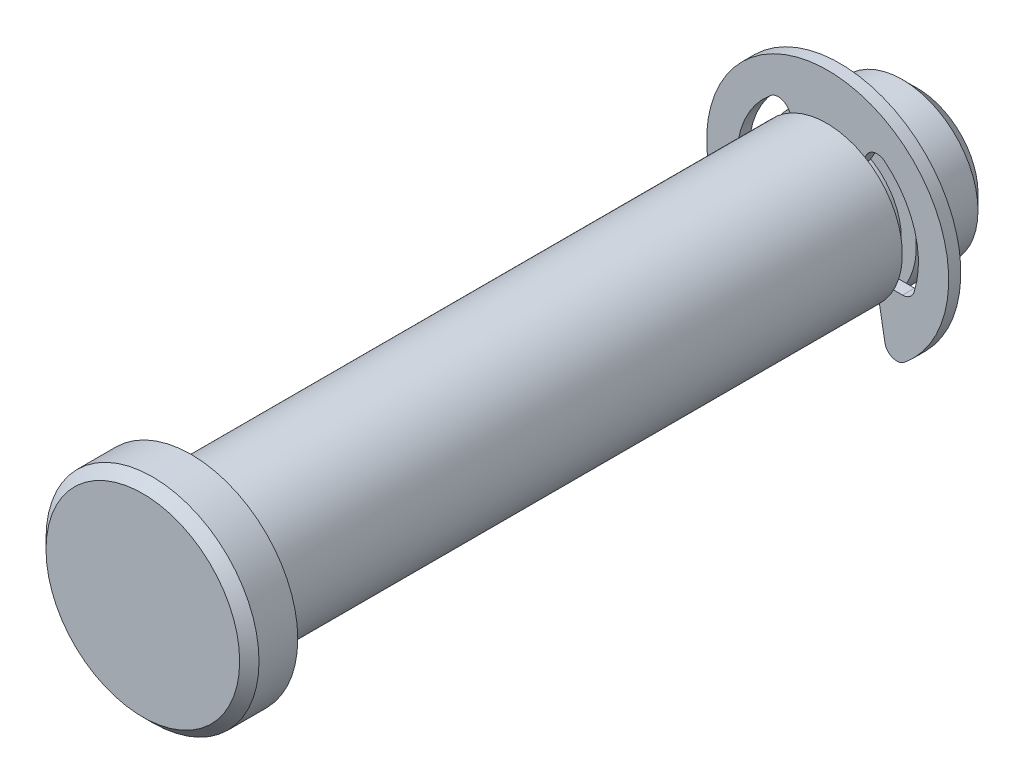
SolidWorks part; units mm, degrees
ref_plane "Front" through (0, 0, 0) normal (0, 0, 1) x (1, 0, 0)
ref_plane "Top" through (0, 0, 0) normal (0, 1, 0) x (1, 0, 0)
ref_plane "Right" through (0, 0, 0) normal (1, 0, 0) x (0, 0, -1)
sketch "Sketch2" plane through (0, 0, 0) normal (0, 0, 1) x (1, 0, 0)
  circle A0 centre (0, 0) radius 3.9688
  point P3 (0, 3.9688)
  point P4 (0, -3.9688)
  dimension "dia" = 7.9375
extrude "Extrude1" add sketch "Sketch2" along normal mid plane 38.1
sketch "Sketch3" plane through (0, 0, 0) normal (1, 0, 0) x (0, 0, -1)
  line L0 (19.05, 3.9688) -> (-19.05, 3.9688) construction
  line L1 (14.2875, 3.9688) -> (15.0241, 3.9688)
  line L2 (14.2875, 3.9688) -> (14.2875, 3.175)
  line L3 (14.2875, 3.175) -> (15.0241, 3.175)
  line L4 (15.0241, 3.9688) -> (15.0241, 3.175)
  line L5 (-19.05, 3.9688) -> (-19.05, -3.9688) construction
  line L10 (15.0241, 3.175) -> (15.0241, -3.175) construction
  point P11 (15.0241, 0)
  point P14 (14.6558, 3.9688)
  dimension "groove wd" = 0.7366
  dimension "groove dia" = 6.35
  dimension "usable lg" = 33.3375
revolve "Cut-Revolve1" cut sketch "Sketch3" angle 360 about axis through (0, 0, 19.05) along (0, 0, -1)
sketch "Sketch8" plane through (0, 0, 19.05) normal (0, 0, 1) x (1, 0, 0)
  circle A0 centre (0, 0) radius 5.588
  dimension "head dia" = 11.176
extrude "Extrude6" add sketch "Sketch8" along normal blind 2.54
chamfer "Chamfer2" distance 0.508 angle 45 1 edges at (5.588, 0, 21.59)
ref_plane "Plane1" through (0, 0, -14.6558) normal (0, 0, 1) x (1, 0, 0)
sketch "Sketch4" plane through (0, 0, -14.6558) normal (0, 0, 1) x (1, 0, 0)
  line L0 (0, 3.175) -> (0, -3.175) construction
  circle A0 centre (0, 0) radius 6.35
  circle A1 centre (0, 0) radius 3.175
  dimension "ring dia" = 12.7
extrude "Extrude2" add sketch "Sketch4" along normal mid plane 0.635 separate body
sketch "Sketch5" plane through (0, 0, 0) normal (0, 0, 1) x (1, 0, 0)
  line L0 (0, 6.35) -> (0, 3.175) construction
  line L1 (-2.3813, 4.1244) -> (0, 0)
  line L2 (-4.3649, -1.905) -> (-2.54, -1.905)
  line L3 (0, 0) -> (2.3813, 4.1244)
  line L4 (-2.54, -1.905) -> (-3.1739, -5.4999)
  line L5 (2.54, -1.905) -> (3.1739, -5.4999)
  line L6 (2.54, -1.905) -> (4.3649, -1.905)
  arc A0 (-2.3813, 4.1244) -> (-4.3649, -1.905) centre (0, 0) ccw
  circle A1 centre (0, 0) radius 6.35 construction
  circle A2 centre (0, 0) radius 3.175 construction
  arc A3 (4.3649, -1.905) -> (2.3813, 4.1244) centre (0, 0) ccw
  arc A4 (-3.1739, -5.4999) -> (3.1739, -5.4999) centre (0, 0) ccw
  circle A5 centre (0, 0) radius 3.175 construction
  point P10 (0, 4.7625)
  dimension "D1" = 30
  dimension "D2" = 10
  dimension "D3" = 1.905
extrude "Extrude4" cut sketch "Sketch5" against normal through all
sketch "Sketch6" plane through (0, 0, -14.3383) normal (0, 0, 1) x (1, 0, 0)
  line L0 (-1.5875, 2.7496) -> (1.5875, 2.7496)
  circle A0 centre (0, 0) radius 3.175 construction
  arc A1 (1.5875, 2.7496) -> (-1.5875, 2.7496) centre (0, 0) ccw
extrude "Extrude5" add sketch "Sketch6" against normal up to surface (0.635 mm away) up to face at (0, 0.8161, -14.9733)
fillet "Fillet1" radius 0.635 6 edges at (3.1739, -5.4999, -14.6558) (-3.1739, -5.4999, -14.6558) (4.3649, -1.905, -14.6558) (2.3813, 4.1244, -14.6558) (-2.3813, 4.1244, -14.6558) (-4.3649, -1.905, -14.6558)
chamfer "Chamfer1" distance 0.7937 angle 45 1 edges at (3.9688, 0, -19.05)
sketch "Sketch7" plane through (0, 0, 0) normal (1, 0, 0) x (0, 0, -1)
  line L0 (14.9733, 6.35) -> (14.3383, 6.35) construction
  line L1 (19.05, -3.9688) -> (19.05, 3.9688) construction
  line L2 (14.3383, -5.0511) -> (14.9733, -5.0511) construction
  line L3 (-21.59, 5.08) -> (-21.59, -5.08) construction
  point P0 (15.0241, -5.0511)
  point P1 (19.05, 3.9688)
  point P2 (-21.59, 5.588)
  point P6 (14.2875, 6.35)
  point P7 (19.05, -3.9688)
  point P12 (-19.05, 5.588)
  point P16 (14.2875, -5.0511)
equation "\"D1@Chamfer1\" = \"dia@Sketch2\" * .1"
equation "\"D1@Fillet1\" = \"ring dia@Sketch4\" * .05"
equation "\"D3@Sketch5\" = \"groove dia@Sketch3\" * .3"
equation "\"D1@Chamfer2\" = \"head ht@Extrude6\" * .2"
